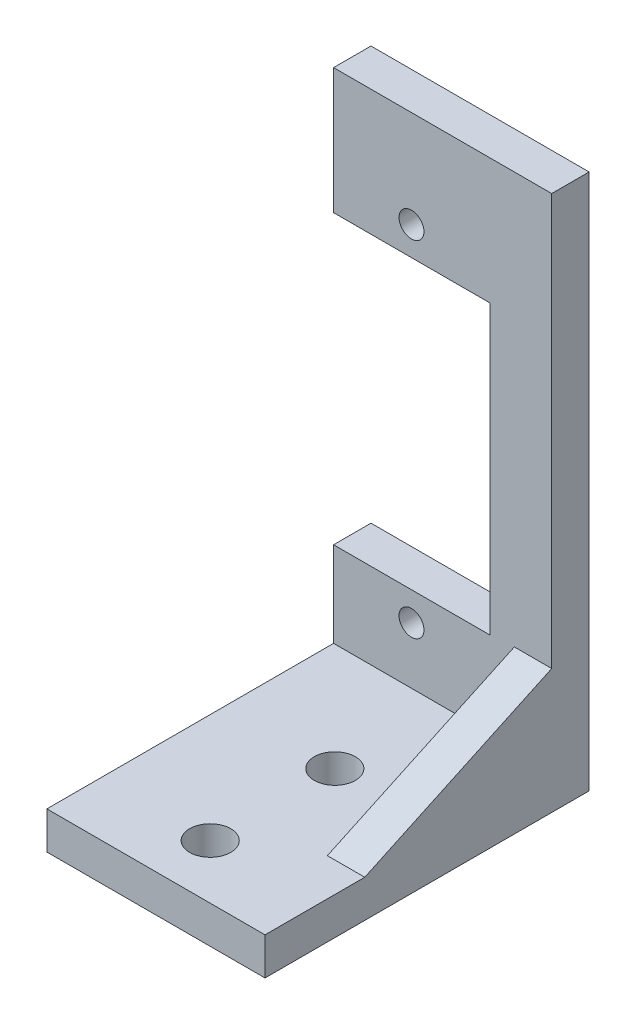
SolidWorks part; units mm, degrees
ref_plane "前视基准面" through (0, 0, 0) normal (0, 0, 1) x (1, 0, 0)
ref_plane "上视基准面" through (0, 0, 0) normal (0, 1, 0) x (1, 0, 0)
ref_plane "右视基准面" through (0, 0, 0) normal (1, 0, 0) x (0, 0, -1)
sketch "草图1" plane through (0, 0, 0) normal (0, 1, 0) x (1, 0, 0)
  line L1 (8.75, -11.5) -> (-8.75, -11.5)
  line L2 (8.75, -11.5) -> (8.75, 11.5)
  line L3 (8.75, 11.5) -> (-8.75, 11.5)
  line L4 (-8.75, -11.5) -> (-8.75, 11.5)
  line L5 (0, 11.5) -> (0, -11.5) construction
  line L6 (8.75, 0) -> (-8.75, 0) construction
  circle A0 centre (0, 2.85) radius 1.65
  circle A1 centre (0, -7.15) radius 1.65
  point P0 (0, 0)
  dimension "D4" = 3.3
  dimension "D5" = 3.3
  dimension "D6" = 10
  dimension "D1" = 17.5
  dimension "D2" = 23
  dimension "D3" = 8.65
extrude "凸台-拉伸1" add sketch "草图1" along normal blind 3
sketch "草图2" plane through (0, 0, 0) normal (0, 1, 0) x (1, 0, 0)
  line L1 (-8.75, 11.5) -> (8.75, 11.5)
  line L2 (-8.75, 11.5) -> (-8.75, 14.5)
  line L3 (-8.75, 14.5) -> (8.75, 14.5)
  line L4 (8.75, 11.5) -> (8.75, 14.5)
  dimension "D1" = 17.5
  dimension "D2" = 3
extrude "凸台-拉伸2" add sketch "草图2" along normal blind 43
sketch "草图3" plane through (0, 0, -14.5) normal (0, 0, -1) x (-1, 0, 0)
  line L0 (-8.75, 0) -> (8.75, 0) construction
  line L1 (8.75, 43) -> (8.75, 0) construction
  line L3 (8.75, 9.85) -> (-3.8, 9.85)
  line L4 (8.75, 9.85) -> (8.75, 32.92)
  line L5 (8.75, 32.92) -> (-3.8, 32.92)
  line L6 (-3.8, 9.85) -> (-3.8, 32.92)
  circle A0 centre (2.5, 7.55) radius 1
  circle A1 centre (2.5, 35.22) radius 1
  dimension "D1" = 2
  dimension "D2" = 7.55
  dimension "D3" = 6.25
  dimension "D4" = 2
  dimension "D5" = 6.25
  dimension "D6" = 27.67
  dimension "D7" = 2.3
  dimension "D8" = 2.3
  dimension "D9" = 12.55
extrude "切除-拉伸1" cut sketch "草图3" against normal up to surface (3 mm away) up to face at (0, 23, -11.5)
sketch "草图4" plane through (8.75, 0, 0) normal (1, 0, 0) x (0, 0, -1)
  line L0 (11.5, 3) -> (-3.5, 3)
  line L1 (-11.5, 3) -> (11.5, 3) construction
  line L2 (-3.5, 3) -> (11.5, 10)
  line L3 (11.5, 43) -> (11.5, 3) construction
  line L4 (11.5, 10) -> (11.5, 3)
  dimension "D1" = 15
  dimension "D2" = 7
extrude "凸台-拉伸3" add sketch "草图4" against normal blind 3
